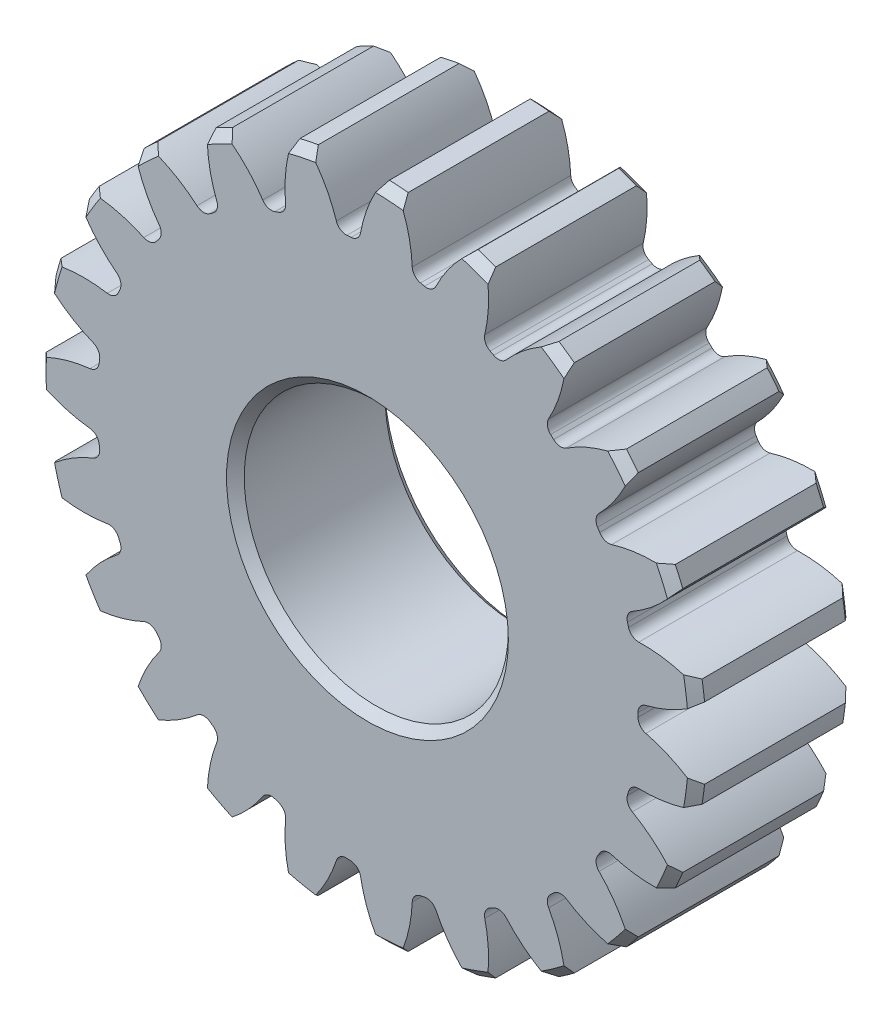
SolidWorks part; units mm, degrees
ref_plane "Front Plane" through (0, 0, 0) normal (0, 0, 1) x (1, 0, 0)
ref_plane "Top Plane" through (0, 0, 0) normal (0, 1, 0) x (1, 0, 0)
ref_plane "Right Plane" through (0, 0, 0) normal (1, 0, 0) x (0, 0, -1)
sketch "Sketch1" plane through (0, 0, 0) normal (0, 0, 1) x (1, 0, 0)
  line L0 (0, 0) -> (0, 2.3) construction
  line L1 (-0.7392, 2.569) -> (0.7392, 2.031) construction
  circle A0 centre (0, 0) radius 2.05 construction
  circle A1 centre (0, 0) radius 2.5 construction
  circle A2 centre (0, 0) radius 2.3 construction
  circle A3 centre (0, 0) radius 2.1613 construction
  circle A5 centre (0, 0) radius 1 construction
  point P8 (0.1, 0)
  point P13 (11.5, 0)
  dimension "OD" = 5
  dimension "Root Diameter" = 4.1
  dimension "Gear Pitch Diameter" = 4.6
  dimension "Base Diameter" = 4.3226
  dimension "For Shaft Diameter" = 2
  dimension "Pressure Angle" = 20
  dimension "Number of Teeth" = 23
  dimension "Module" = 0.2
sketch "Sketch2" plane through (0, 0, 0) normal (1, 0, 0) x (0, 0, -1)
  line L0 (-0.6, 0) -> (0.6, 0) construction
  line L1 (0.6, 2.5) -> (0.6, -2.5) construction
  line L3 (-0.6, 2.5) -> (0.6, 2.5) construction
  line L5 (-0.6, 12.5) -> (-0.6, -12.5) construction
  point P2 (0, 2.5)
  dimension "Overall Width" = 1.2
  dimension "Face Width" = 0.6
sketch "Sketch3" plane through (0, 0, 0) normal (0, 0, 1) x (1, 0, 0)
  circle A0 centre (0, 0) radius 2.5
  circle A1 centre (0, 0) radius 2.5 construction
extrude "Boss-Extrude1" add sketch "Sketch3" against normal up to vertex (0.6 mm away) and the other way up to vertex (0.6 mm away) up to point (0, 0, -0.6) other way up to point (0, 0, 0.6)
sketch "Sketch5" plane through (0, 0, 0) normal (1, 0, 0) x (0, 0, -1)
  line L5 (-0.6, 0) -> (0.6, 0)
  line L6 (-0.6, 0) -> (-0.6, 1)
  line L7 (-0.6, 1) -> (0.6, 1)
  line L8 (0.6, 0) -> (0.6, 1)
  point P12 (0, 1)
revolve "Cut-Revolve1" cut sketch "Sketch5" angle 360 about L0
chamfer "Chamfer2" distance 0.0671 angle 45 4 edges at (2.5, 0, -0.6) (1, 0, -0.6) (1, 0, 0.6) (2.5, 0, 0.6)
sketch "Sketch4" plane through (0, 0, 0) normal (0, 0, 1) x (1, 0, 0)
  line L0 (2.0485, -0.0785) -> (2.0485, 0.0785)
  arc A3 (2.4854, 0.2699) -> (2.4854, -0.2699) centre (0, 0) cw
  circle A4 centre (0, 0) radius 2.5 construction
  arc A5 (2.4854, 0.2699) -> (2.0485, 0.0785) centre (1.8432, 1.1419) cw
  circle A6 centre (0, 0) radius 2.05 construction
  arc A7 (2.4854, -0.2699) -> (2.0485, -0.0785) centre (1.8432, -1.1419) ccw
  spline S0 degree 4 poles (2.1582, 0.1153) (2.1588, 0.1154) (2.1603, 0.1155) (2.1631, 0.1158) (2.1678, 0.1164) (2.1737, 0.1174) (2.1813, 0.1188) (2.1902, 0.1207) (2.2, 0.1231) (2.2106, 0.126) (2.2211, 0.1291) (2.2316, 0.1324) (2.242, 0.136) (2.2546, 0.1405) (2.2696, 0.1463) (2.287, 0.1535) (2.3067, 0.1623) (2.3266, 0.1718) (2.346, 0.1818) (2.3656, 0.1923) (2.3844, 0.203) (2.4037, 0.2147) (2.4216, 0.2258) (2.4412, 0.2388) (2.4573, 0.2496) (2.4822, 0.2674) (2.4928, 0.2753) (2.5088, 0.2874) (2.5141, 0.2916) knots 0 0 0 0 0 0.005377 0.015084 0.028532 0.04661 0.064855 0.092111 0.119476 0.146842 0.174209 0.201575 0.228941 0.256307 0.307035 0.361767 0.4165 0.471232 0.525964 0.580697 0.635429 0.690161 0.744894 0.799626 0.854358 0.909091 1 1 1 1 1 construction
  spline S1 degree 4 poles (2.1582, 0.1153) (2.1588, 0.1154) (2.1603, 0.1155) (2.1631, 0.1158) (2.1678, 0.1164) (2.1737, 0.1174) (2.1813, 0.1188) (2.1902, 0.1207) (2.2, 0.1231) (2.2106, 0.126) (2.2211, 0.1291) (2.2316, 0.1324) (2.242, 0.136) (2.2546, 0.1405) (2.2696, 0.1463) (2.287, 0.1535) (2.3067, 0.1623) (2.3266, 0.1718) (2.346, 0.1818) (2.3656, 0.1923) (2.3844, 0.203) (2.4037, 0.2147) (2.4216, 0.2258) (2.4412, 0.2388) (2.4573, 0.2496) (2.4734, 0.2611) (2.4814, 0.2669) (2.4854, 0.2699) knots 0 0 0 0 0 0.005377 0.015084 0.028532 0.04661 0.064855 0.092111 0.119476 0.146842 0.174209 0.201575 0.228941 0.256307 0.307035 0.361767 0.4165 0.471232 0.525964 0.580697 0.635429 0.690161 0.744894 0.799626 0.854358 0.909091 0.909091 0.909091 0.909091 0.909091 construction
  spline S2 degree 4 poles (2.1582, -0.1153) (2.1588, -0.1154) (2.1603, -0.1155) (2.1631, -0.1158) (2.1678, -0.1164) (2.1737, -0.1174) (2.1813, -0.1188) (2.1902, -0.1207) (2.2, -0.1231) (2.2106, -0.126) (2.2211, -0.1291) (2.2316, -0.1324) (2.242, -0.136) (2.2546, -0.1405) (2.2696, -0.1463) (2.287, -0.1535) (2.3067, -0.1623) (2.3266, -0.1718) (2.346, -0.1818) (2.3656, -0.1923) (2.3844, -0.203) (2.4037, -0.2147) (2.4216, -0.2258) (2.4412, -0.2388) (2.4573, -0.2496) (2.4822, -0.2674) (2.4928, -0.2753) (2.5088, -0.2874) (2.5141, -0.2916) knots 0 0 0 0 0 0.005377 0.015084 0.028532 0.04661 0.064855 0.092111 0.119476 0.146842 0.174209 0.201575 0.228941 0.256307 0.307035 0.361767 0.4165 0.471232 0.525964 0.580697 0.635429 0.690161 0.744894 0.799626 0.854358 0.909091 1 1 1 1 1 construction
  spline S3 degree 4 poles (2.1582, -0.1153) (2.1588, -0.1154) (2.1603, -0.1155) (2.1631, -0.1158) (2.1678, -0.1164) (2.1737, -0.1174) (2.1813, -0.1188) (2.1902, -0.1207) (2.2, -0.1231) (2.2106, -0.126) (2.2211, -0.1291) (2.2316, -0.1324) (2.242, -0.136) (2.2546, -0.1405) (2.2696, -0.1463) (2.287, -0.1535) (2.3067, -0.1623) (2.3266, -0.1718) (2.346, -0.1818) (2.3656, -0.1923) (2.3844, -0.203) (2.4037, -0.2147) (2.4216, -0.2258) (2.4412, -0.2388) (2.4573, -0.2496) (2.4734, -0.2611) (2.4814, -0.2669) (2.4854, -0.2699) knots 0 0 0 0 0 0.005377 0.015084 0.028532 0.04661 0.064855 0.092111 0.119476 0.146842 0.174209 0.201575 0.228941 0.256307 0.307035 0.361767 0.4165 0.471232 0.525964 0.580697 0.635429 0.690161 0.744894 0.799626 0.854358 0.909091 0.909091 0.909091 0.909091 0.909091 construction
  dimension "D1" = 0.1571
extrude "Cut-Extrude1" cut sketch "Sketch4" against normal through all both and the other way through all
fillet "Fillet1" radius 0.0785 2 edges at (2.0485, -0.0785, 0) (2.0485, 0.0785, 0)
pattern_circular "CirPattern1" count 23 over 360 about axis through (0, 0, 0) along (0, 0, 1) of "Cut-Extrude1", "Fillet1"
equation "\"Number of Teeth\"= 23"
equation "\"Module\"= 0.2"
equation "\"Diametral Pitch\"= 1 / \"Module\""
equation "\"Dedendum\"= 1.25 / \"Diametral Pitch\""
equation "\"Pitch Diameter\"= \"Module\" * \"Number of Teeth\""
equation "\"Root Diameter\"= \"Pitch Diameter\" - ( 2 * \"Dedendum\" )"
equation "\"Root Diameter@Sketch1\"=\"Root Diameter\""
equation "\"OD@Sketch1\" = \"Outside Diameter\""
equation "\"D1@CirPattern1\"=\"Number of Teeth\""
equation "\"Pressure Angle\"= 20"
equation "\"Base Diameter\"= \"Pitch Diameter\" * cos ( \"Pressure Angle\" )"
equation "\"Outside Diameter\"= ( \"Number of Teeth\" + 2 ) / \"Diametral Pitch\""
equation "\"Pitch Angle\"= 360deg / \"Number of Teeth\""
equation "\"Alpha\"= sqr ( \"Pitch Diameter\" ^ 2 - \"Base Diameter\" ^ 2 ) / \"Base Diameter\" * 180 / PI - \"Pressure Angle\""
equation "\"Beta\"= ( \"Pitch Angle\" / 4 - \"Alpha\" )"
equation "\"Phi\"= sqr ( ( \"Outside Diameter\" / 2 ) ^ 2 - ( \"Base Diameter\" / 2 ) ^ 2 ) / ( \"Base Diameter\" / 2 )"
equation "\"Addendum\"= 1 / \"Diametral Pitch\""
equation "\"WorkingDepth\"= 2 / \"Diametral Pitch\""
equation "\"WholeDepth\"= 2.25 / \"Diametral Pitch\""
equation "\"Clearance\"= 0.25 / \"Diametral Pitch\""
equation "\"ToothThickness\"= ( pi * 2 ) / \"Diametral Pitch\""
equation "\"CircularPitch\"= pi / \"Diametral Pitch\""
equation "\"Number of Teeth@Sketch1\"=\"Number of Teeth\""
equation "\"Module@Sketch1\"=\"Module\""
equation "\"Pressure Angle@Sketch1\"=\"Pressure Angle\""
equation "\"Gear Pitch Diameter@Sketch1\"=\"Pitch Diameter\""
equation "\"Base Diameter@Sketch1\"=\"Base Diameter\""
equation "\"Fillet\"= \"Clearance\" * cos ( \"Pressure Angle\" ) * tan ( ( 90 + \"Pressure Angle\" ) / 2 )"
equation "\"D1\"= \"Fillet\""
equation "\"D1\"= \"Set Screw Pitch@Sketch1\" * .75"
equation "\"D1\"= \"Set Screw Diameter@Sketch1\" / 2"
equation "\"D3\"= \"Set Screw Pitch@Sketch1\" +  ( \"Hub Diameter@Sketch1\" / 2 ) "
equation "\"D4\"= \"Set Screw Pitch@Sketch1\""
equation "\"D2\"= \"Fillet\" * 2"
equation "\"D1\"= \"Fillet\" * 2"
equation "\"D1@Chamfer2\"=\"Fillet\""
equation "\"D1@Sketch4\"=\"CircularPitch\"*0.25"
equation "\"D1@Fillet1\"=\"CircularPitch\"*0.125"
